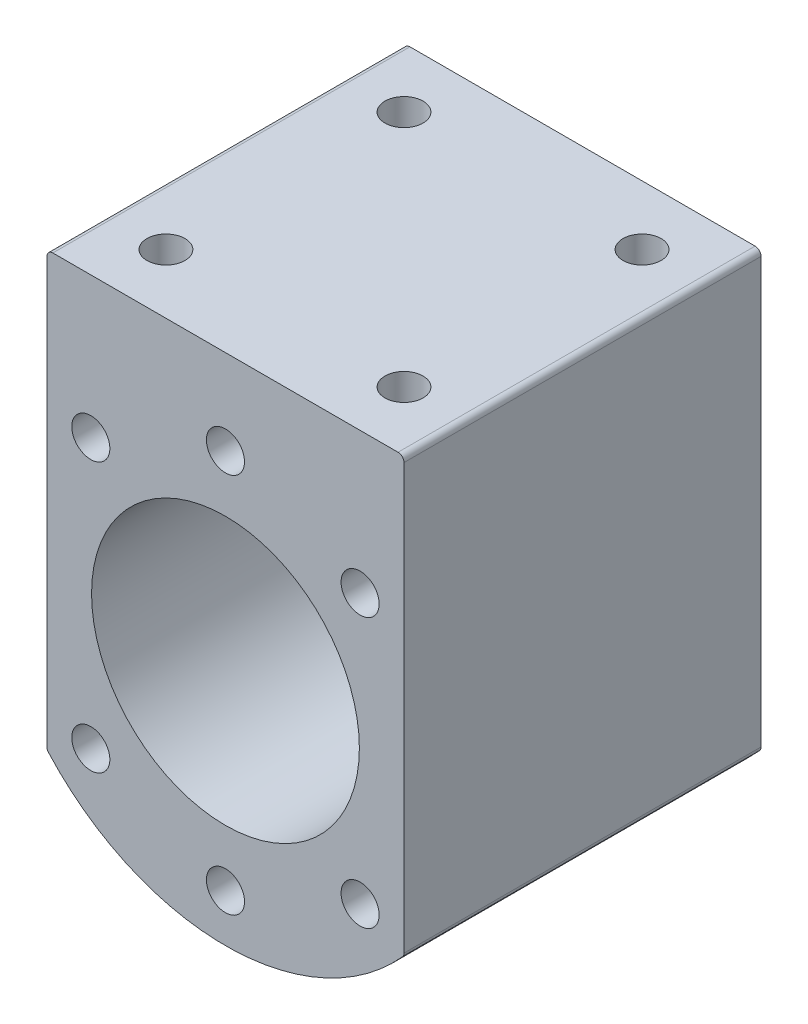
SolidWorks part; units mm, degrees
ref_plane "Front" through (0, 0, 0) normal (0, 0, 1) x (1, 0, 0)
ref_plane "Top" through (0, 0, 0) normal (0, 1, 0) x (1, 0, 0)
ref_plane "Right" through (0, 0, 0) normal (1, 0, 0) x (0, 0, -1)
sketch "Sketch1" plane through (0, 0, 0) normal (0, 0, 1) x (1, 0, 0)
  line L0 (-15, 23.1512) -> (-15, -13.2288)
  line L1 (15, 23.1512) -> (15, -13.2288)
  line L2 (0, -50) -> (0, 50) construction
  line L3 (0, 0) -> (0, 28.2531) construction
  line L4 (15, 23.1512) -> (-15, 23.1512)
  arc A1 (-15, -13.2288) -> (15, -13.2288) centre (0, 0) ccw
  dimension "D1" = 30
  dimension "D2" = 36.38
extrude "Boss-Extrude1" add sketch "Sketch1" along normal blind 30
sketch "Sketch2" plane through (0, 0, 0) normal (0, 0, -1) x (-1, 0, 0)
  circle A0 centre (0, 0) radius 11.25
  dimension "D1" = 22.5
sketch "Sketch4" plane through (0, 0, 0) normal (0, 0, -1) x (-1, 0, 0)
  line L0 (-11.3137, 11.3137) -> (0, 0) construction
  line L1 (0, 0) -> (0, 16) construction
  line L2 (11.3137, 11.3137) -> (0, 0) construction
  circle A0 centre (0, 0) radius 16 construction
  circle A1 centre (-11.3137, 11.3137) radius 1.6
  circle A2 centre (0, 16) radius 1.6
  circle A3 centre (11.3137, 11.3137) radius 1.6
  dimension "D1" = 32
  dimension "D2" = 3.2
  dimension "D3" = 45
  dimension "D4" = 45
extrude "Cut-Extrude2" cut sketch "Sketch4" against normal blind 20 from offset 20 offset against normal yes
mirror "Mirror1" about plane through (0, 0, 0) normal (0, 1, 0) of "Cut-Extrude2"
extrude "Cut-Extrude3" cut sketch "Sketch2" against normal blind 30
sketch "Sketch5" plane through (0, 23.1512, 0) normal (0, 1, 0) x (1, 0, 0)
  line L0 (15, -30) -> (-15, -30) construction
  line L1 (-15, -30) -> (-15, 0) construction
  line L2 (0, -30) -> (0, -5.7919) construction
  line L3 (-15, -15) -> (15, -15) construction
  line L4 (15, -30) -> (15, 0) construction
  circle A0 centre (10, -25) radius 1.6
  circle A1 centre (-10, -25) radius 1.6
  circle A2 centre (10, -5) radius 1.6
  circle A3 centre (-10, -5) radius 1.6
  dimension "D1" = 3.2
  dimension "D2" = 5
  dimension "D3" = 5
extrude "Cut-Extrude4" cut sketch "Sketch5" against normal blind 9
fillet "Fillet1" radius 0.5 4 edges at (-15, -13.2288, 15) (15, -13.2288, 15) (-15, 23.1512, 15) (15, 23.1512, 15)
equation "\"flange_d\"= 40"
equation "\"flange_b\"= 30"
equation "\"flange_h\"=30"
equation "\"nut_h\"= 40"
equation "\"nut_d\"=22.5"
equation "\"d\"= 12"
equation "\"screws_d\"=3.2"
equation "\"screws_placement_d\"= 32"
equation "\"D1@Sketch1\"=\"flange_b\""
equation "\"D1@Boss-Extrude1\"=\"flange_h\""
equation "\"D1@Sketch2\"=\"nut_d\""
equation "\"D1@Sketch4\"=\"screws_placement_d\""
equation "\"D2@Sketch4\"=\"screws_d\""
equation "\"D4@Sketch4\"=\"D3@Sketch4\""
